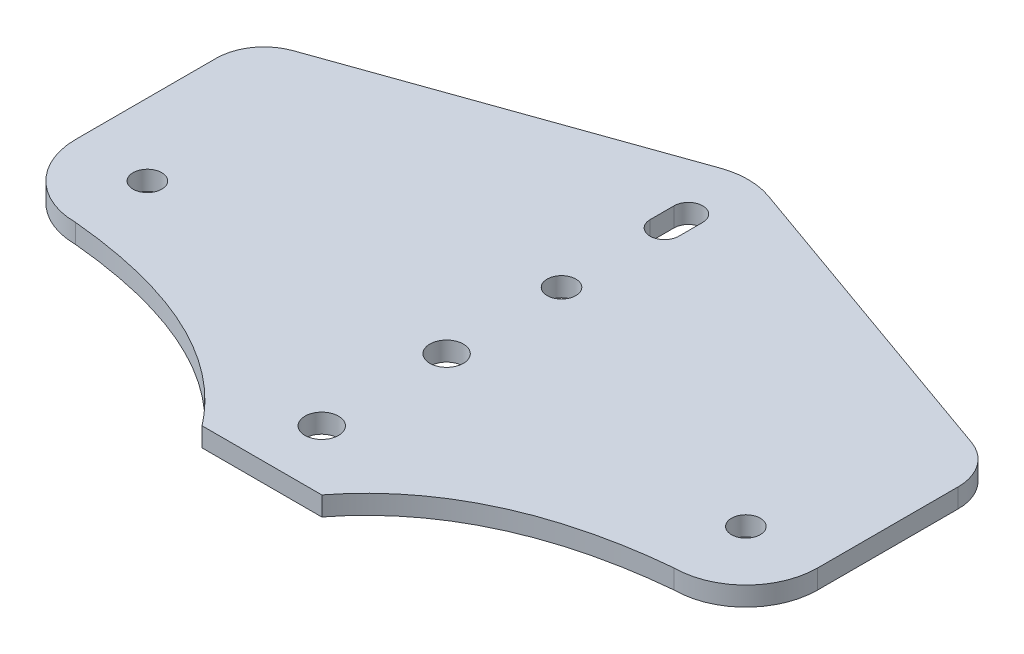
SolidWorks part; units mm, degrees
ref_plane "Front Plane" through (0, 0, 0) normal (0, 0, 1) x (1, 0, 0)
ref_plane "Top Plane" through (0, 0, 0) normal (0, 1, 0) x (1, 0, 0)
ref_plane "Right Plane" through (0, 0, 0) normal (1, 0, 0) x (0, 0, -1)
sketch "Bearing Reference" plane through (0, 0, 0) normal (0, 1, 0) x (1, 0, 0)
  line L0 (-88.9075, -9.8626) -> (103.9529, -9.8626) construction
  line L1 (-85.5461, -34.8626) -> (101.4318, -34.8626) construction
  circle A1 centre (58.784, -46.2837) radius 12
  circle A2 centre (-66.216, -46.2837) radius 12
  circle A3 centre (-3.716, 1.7163) radius 12
  point P2 (58.784, -46.2837)
  point P11 (0, 0)
  dimension "D2" = 24
  dimension "D3" = 24
  dimension "D4" = 24
  dimension "D1" = 25
  dimension "D5" = 125
  dimension "D6" = 62.5
  dimension "D7" = 48
  dimension "D8" = 48
sketch "Sketch2" plane through (0, 0, 0) normal (0, 1, 0) x (1, 0, 0)
  line L6 (-3.716, 4.2163) -> (-3.716, -0.7837) construction
  line L7 (-88.9075, -9.8626) -> (103.9529, -9.8626) construction
  line L8 (101.4318, -34.8626) -> (-85.5461, -34.8626) construction
  line L9 (-66.216, -46.2837) -> (58.784, -46.2837) construction
  line L10 (-3.716, -46.2837) -> (-3.716, 1.7163) construction
  line L15 (-81.216, -46.2837) -> (-81.216, -16.9256)
  line L16 (-74.5595, -7.5011) -> (-8.7313, 15.853)
  line L17 (73.784, -46.2837) -> (73.784, -16.9256)
  line L18 (67.1276, -7.5011) -> (1.2994, 15.853)
  line L19 (-16.216, -34.8626) -> (8.784, -34.8626) construction
  line L20 (-16.216, -22.3626) -> (8.784, -22.3626) construction
  line L21 (-16.216, -22.3626) -> (-16.216, -72.3626) construction
  line L22 (-16.216, -72.3626) -> (8.784, -72.3626) construction
  line L23 (8.784, -22.3626) -> (8.784, -72.3626) construction
  line L24 (-16.216, -34.8626) -> (-16.216, -84.8626) construction
  line L25 (-16.216, -84.8626) -> (8.784, -84.8626)
  line L26 (8.784, -34.8626) -> (8.784, -84.8626) construction
  line L27 (-0.716, 4.2163) -> (-0.716, -0.7837)
  line L28 (-6.716, 4.2163) -> (-6.716, -0.7837)
  arc A0 (-81.216, -46.2837) -> (-66.216, -61.2837) centre (-66.216, -46.2837) ccw
  arc A1 (1.2994, 15.853) -> (-8.7313, 15.853) centre (-3.716, 1.7163) ccw
  arc A2 (58.784, -61.2837) -> (73.784, -46.2837) centre (58.784, -46.2837) ccw
  circle A3 centre (-66.216, -46.2837) radius 3
  circle A4 centre (58.784, -46.2837) radius 3
  arc A6 (73.784, -16.9256) -> (67.1276, -7.5011) centre (63.784, -16.9256) ccw
  arc A7 (-81.216, -16.9256) -> (-74.5595, -7.5011) centre (-71.216, -16.9256) cw
  arc A16 (-0.716, 4.2163) -> (-6.716, 4.2163) centre (-3.716, 4.2163) ccw
  arc A17 (-6.716, -0.7837) -> (-0.716, -0.7837) centre (-3.716, -0.7837) ccw
  circle A19 centre (-3.716, -46.2837) radius 3.5
  circle A20 centre (-3.716, -72.3626) radius 3.5
  circle A21 centre (-3.716, -22.2837) radius 3
  spline S0 degree 2 poles (-66.216, -61.2837) (-31.9884, -64.4698) (-16.216, -84.8626) knots 0 0 0 0.615675 0.615675 0.615675
  spline S1 degree 2 poles (58.784, -61.2837) (24.5565, -64.4698) (8.784, -84.8626) knots 0 0 0 0.615675 0.615675 0.615675
  point P51 (73.784, -9.8626)
  point P54 (-81.216, -9.8626)
  point P75 (-3.716, 1.7163)
  dimension "D1" = 30
  dimension "D2" = 30
  dimension "D3" = 30
  dimension "D8" = 6
  dimension "D10" = 6
  dimension "D15" = 10
  dimension "D19" = 3
  dimension "D20" = 7
  dimension "D21" = 7
  dimension "D4" = 6
  dimension "D11" = 25
  dimension "D12" = 50
  dimension "D13" = 12.5
  dimension "D14" = 50
  dimension "D16" = 25
  dimension "D18" = 5
extrude "MainPlateExtrude" add sketch "Sketch2" along normal blind 4
